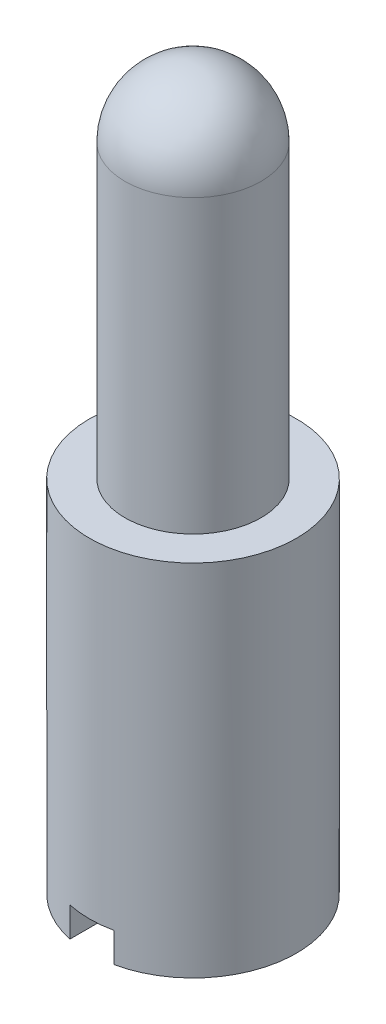
SolidWorks part; units mm, degrees
material "Chrome Stainless Steel"
ref_plane "Front Plane" through (0, 0, 0) normal (0, 0, 1) x (1, 0, 0)
ref_plane "Top Plane" through (0, 0, 0) normal (0, 1, 0) x (1, 0, 0)
ref_plane "Right Plane" through (0, 0, 0) normal (1, 0, 0) x (0, 0, -1)
sketch "Sketch1" plane through (0, 0, 0) normal (0, 0, 1) x (1, 0, 0)
  line L0 (0, 19.05) -> (0, 0)
  line L1 (0, 0) -> (2.7432, 0)
  line L2 (2.7432, 0) -> (2.7432, 9.525)
  line L3 (2.7432, 9.525) -> (1.8034, 9.525)
  line L4 (1.8034, 9.525) -> (1.8034, 17.2466)
  arc A0 (1.8034, 17.2466) -> (0, 19.05) centre (0, 17.2466) ccw
  point P8 (0, 0)
  dimension "D1" = 19.05
  dimension "D2" = 9.525
  dimension "D3" = 2.7432
  dimension "D4" = 1.8034
revolve "Revolve1" add sketch "Sketch1" angle 360 about L0
cosmetic thread "Cosmetic Thread1" parameters "D2"=4.2266
sketch "Sketch2" plane through (0, 0, 0) normal (0, -1, 0) x (1, 0, 0)
  line L1 (-0.5842, -3.0826) -> (0.5842, -3.0826)
  line L2 (-0.5842, -3.0826) -> (-0.5842, 3.0826)
  line L3 (-0.5842, 3.0826) -> (0.5842, 3.0826)
  line L4 (0.5842, -3.0826) -> (0.5842, 3.0826)
  line L5 (-0.5842, -3.0826) -> (0.5842, 3.0826) construction
  line L6 (-0.5842, 3.0826) -> (0.5842, -3.0826) construction
  point P0 (0, 0)
  dimension "D1" = 1.1684
extrude "Cut-Extrude1" cut sketch "Sketch2" against normal blind 0.7874
